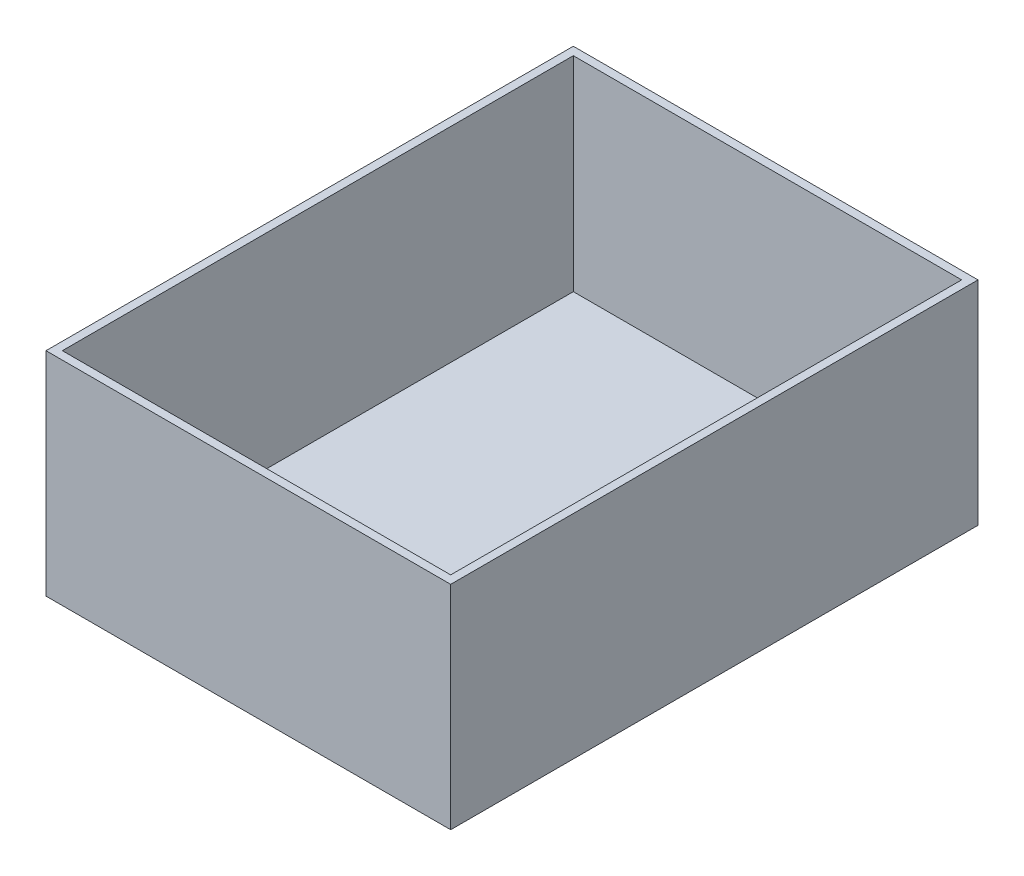
SolidWorks part; units mm, degrees
ref_plane "Front Plane" through (0, 0, 0) normal (0, 0, 1) x (1, 0, 0)
ref_plane "Top Plane" through (0, 0, 0) normal (0, 1, 0) x (1, 0, 0)
ref_plane "Right Plane" through (0, 0, 0) normal (1, 0, 0) x (0, 0, -1)
sketch "Sketch2" plane through (0, 0, 0) normal (0, 1, 0) x (1, 0, 0)
  line L0 (-49.5, 64.5) -> (-49.5, -64.5)
  line L1 (-47.5, 62.5) -> (47.5, 62.5)
  line L2 (-47.5, 62.5) -> (-47.5, -62.5)
  line L3 (-47.5, -62.5) -> (47.5, -62.5)
  line L4 (47.5, 62.5) -> (47.5, -62.5)
  line L5 (-47.5, 62.5) -> (47.5, -62.5) construction
  line L6 (-47.5, -62.5) -> (47.5, 62.5) construction
  line L7 (-49.5, -64.5) -> (49.5, -64.5)
  line L8 (49.5, 64.5) -> (49.5, -64.5)
  line L9 (-49.5, 64.5) -> (49.5, 64.5)
  point P0 (0, 0)
  dimension "D1" = 125
  dimension "D2" = 95
  dimension "D3" = 2
extrude "Walls" add sketch "Sketch2" along normal blind 50
sketch "Sketch3" plane through (0, 0, 0) normal (0, -1, 0) x (1, 0, 0)
  line L1 (-49.5, -64.5) -> (49.5, -64.5)
  line L2 (-49.5, -64.5) -> (-49.5, 64.5)
  line L3 (-49.5, 64.5) -> (49.5, 64.5)
  line L4 (49.5, -64.5) -> (49.5, 64.5)
  line L5 (-49.5, -64.5) -> (49.5, 64.5) construction
  line L6 (-49.5, 64.5) -> (49.5, -64.5) construction
  point P0 (0, 0)
extrude "Base" add sketch "Sketch3" along normal blind 2
